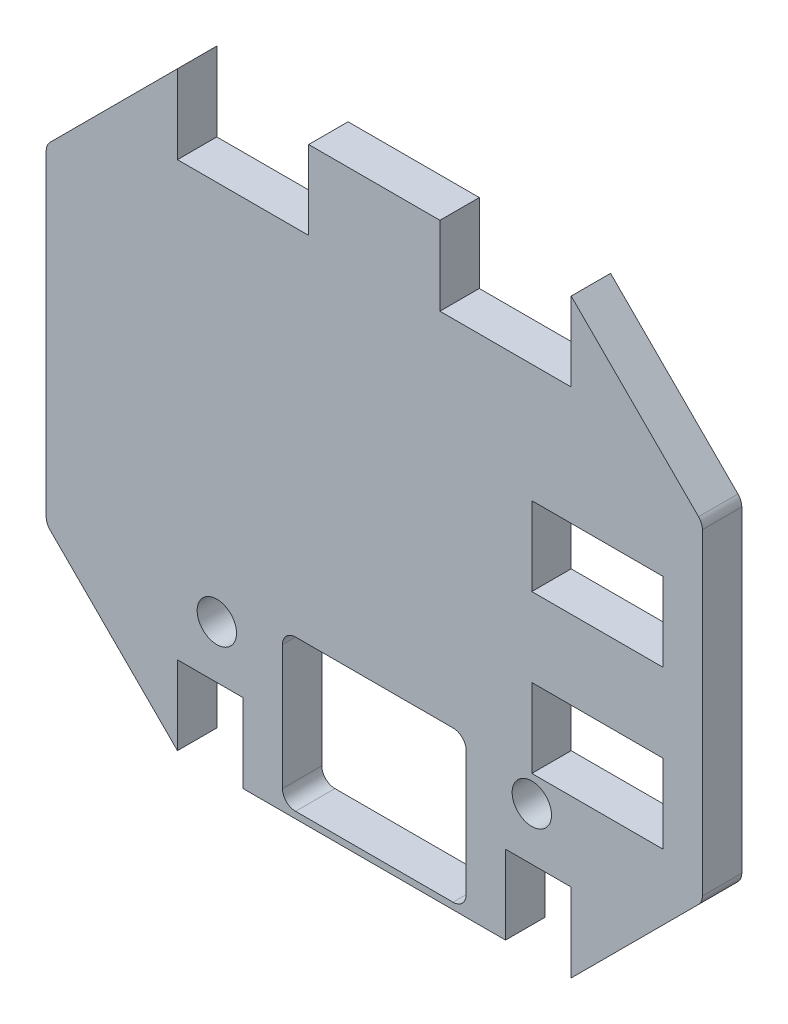
SolidWorks part; units mm, degrees
ref_plane "Front Plane" through (0, 0, 0) normal (0, 0, 1) x (1, 0, 0)
ref_plane "Top Plane" through (0, 0, 0) normal (0, 1, 0) x (1, 0, 0)
ref_plane "Right Plane" through (0, 0, 0) normal (1, 0, 0) x (0, 0, -1)
sketch "Sketch1" plane through (0, 0, 0) normal (0, 0, 1) x (1, 0, 0)
  line L0 (0, 0) -> (0, 25)
  line L1 (0, 25) -> (10, 35)
  line L2 (10, 35) -> (40, 35)
  line L3 (40, 35) -> (50, 25)
  line L4 (50, 25) -> (50, 0)
  line L5 (50, 0) -> (40, -10)
  line L6 (40, -10) -> (10, -10)
  line L7 (10, -10) -> (0, 0)
  line L9 (18, 2) -> (32, 2)
  line L10 (18, 2) -> (18, -9.5)
  line L11 (18, -9.5) -> (32, -9.5)
  line L12 (32, 2) -> (32, -9.5)
  circle A0 centre (13, 0) radius 1.5
  circle A1 centre (37, 0) radius 1.5
  dimension "D3" = 3
  dimension "D2" = 10
  dimension "D1" = 45
  dimension "D4" = 24
  dimension "D5" = 14
  dimension "D6" = 11.5
  dimension "D7" = 5
  dimension "D8" = 2
  dimension "D15" = 50
  dimension "D16" = 30
  dimension "D17" = 18
extrude "Boss-Extrude1" add sketch "Sketch1" along normal blind 3
sketch "Sketch2" plane through (0, 0, 3) normal (0, 0, 1) x (1, 0, 0)
  line L0 (10, -10) -> (40, -10) construction
  line L1 (10, 35) -> (20, 35)
  line L2 (10, 35) -> (10, 29)
  line L3 (10, 29) -> (20, 29)
  line L4 (20, 35) -> (20, 29)
  line L5 (30, 35) -> (40, 35)
  line L6 (30, 35) -> (30, 29)
  line L7 (30, 29) -> (40, 29)
  line L8 (40, 35) -> (40, 29)
  line L9 (10, -4) -> (15, -4)
  line L10 (10, -4) -> (10, -10)
  line L11 (10, -10) -> (15, -10)
  line L12 (15, -4) -> (15, -10)
  line L13 (35, -4) -> (40, -4)
  line L14 (35, -4) -> (35, -10)
  line L15 (35, -10) -> (40, -10)
  line L16 (40, -4) -> (40, -10)
  line L17 (40, 35) -> (10, 35) construction
  dimension "D1" = 6
  dimension "D2" = 10
  dimension "D3" = 5
  dimension "D4" = 30
extrude "Cut-Extrude1" cut sketch "Sketch2" against normal through all
sketch "Sketch3" plane through (0, 0, 3) normal (0, 0, 1) x (1, 0, 0)
  line L0 (32, 2) -> (18, 2) construction
  line L1 (37, 8) -> (47, 8)
  line L2 (37, 8) -> (37, 2)
  line L3 (37, 2) -> (47, 2)
  line L4 (47, 8) -> (47, 2)
  line L5 (50, 0) -> (50, 25) construction
  line L7 (37, 20) -> (47, 20)
  line L8 (37, 20) -> (37, 14)
  line L9 (37, 14) -> (47, 14)
  line L10 (47, 20) -> (47, 14)
  dimension "D1" = 10
  dimension "D2" = 6
  dimension "D3" = 0
  dimension "D4" = 3
  dimension "D5" = 6
extrude "Cut-Extrude2" cut sketch "Sketch3" against normal through all
fillet "Fillet1" radius 1 8 edges at (18, 2, 1.5) (18, -9.5, 1.5) (32, 2, 1.5) (32, -9.5, 1.5) (50, 0, 1.5) (50, 25, 1.5) (0, 25, 1.5) (0, 0, 1.5)
